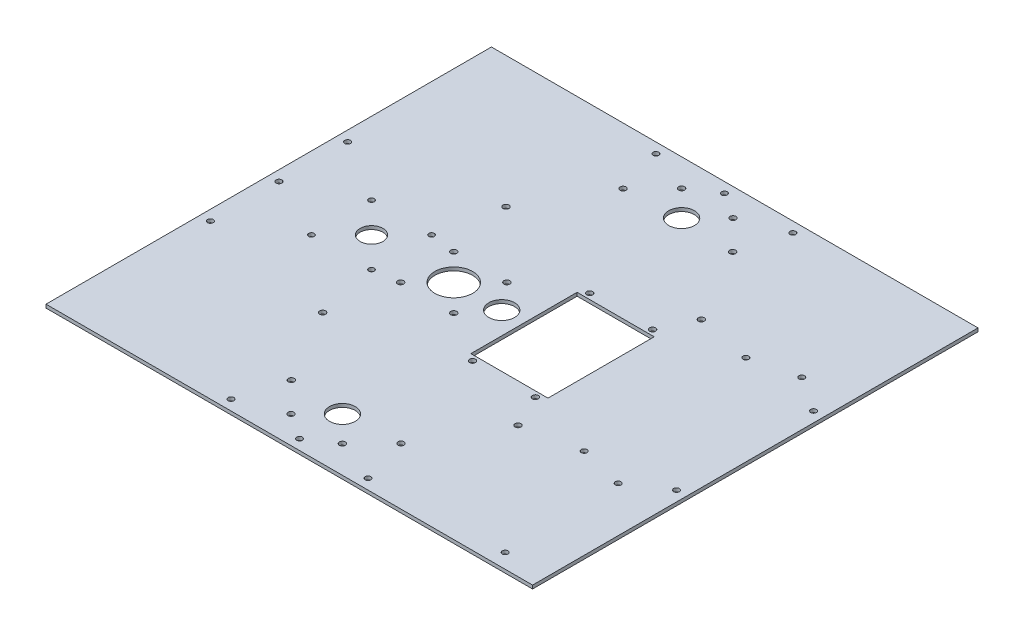
SolidWorks part; units mm, degrees
ref_plane "前视基准面" through (0, 0, 0) normal (0, 0, 1) x (1, 0, 0)
ref_plane "上视基准面" through (0, 0, 0) normal (0, 1, 0) x (1, 0, 0)
ref_plane "右视基准面" through (0, 0, 0) normal (1, 0, 0) x (0, 0, -1)
sketch "草图1" plane through (0, 0, 0) normal (0, 1, 0) x (1, 0, 0)
  line L0 (0, 130) -> (0, -35.361) construction
  line L1 (-142, -130) -> (142, -130)
  line L2 (-142, -130) -> (-142, 130)
  line L3 (-142, 130) -> (142, 130)
  line L5 (-142, 0) -> (204.6664, 0) construction
  line L10 (142, -130) -> (142, 130)
  dimension "D1" = 284
  dimension "D2" = 260
extrude "凸台-拉伸1" add sketch "草图1" along normal blind 2
sketch "草图2" plane through (0, 2, 0) normal (0, 1, 0) x (1, 0, 0)
  line L0 (-142, -130) -> (-142, 130) construction
  line L1 (-142, 0) -> (101.1534, 0) construction
  line L2 (-82, 0) -> (-86.8462, 4.8462) construction
  line L3 (142, 0) -> (52, 0) construction
  line L8 (50.3891, 31) -> (5.3891, -31) construction
  line L10 (-34, 21.5187) -> (-34, -23.7544) construction
  line L16 (52, -31) -> (7, -31)
  line L17 (52, -31) -> (52, 31)
  line L18 (52, 31) -> (7, 31)
  line L19 (-142, 130) -> (142, 130) construction
  line L20 (142, -130) -> (142, 130) construction
  line L21 (7, -31) -> (7, 31)
  line L24 (47.8891, 0) -> (29.5391, 0) construction
  line L25 (11.15, -34.2) -> (47.85, -34.2) construction
  line L26 (11.15, -34.2) -> (11.15, 34.2) construction
  circle A0 centre (-82, 0) radius 6.65
  circle A2 centre (-99.5362, 17.5362) radius 1.6
  circle A3 centre (-64.4638, 17.5362) radius 1.6
  circle A4 centre (-64.4638, -17.5362) radius 1.6
  circle A5 centre (-99.5362, -17.5362) radius 1.6
  circle A10 centre (-34, 0) radius 11.05
  circle A11 centre (-18.5, 15.5) radius 1.75
  circle A12 centre (-18.5, -15.5) radius 1.75
  circle A13 centre (-49.5, -15.5) radius 1.75
  circle A14 centre (-49.5, 15.5) radius 1.75
  circle A17 centre (-40, 124) radius 1.65
  circle A18 centre (0, 124) radius 1.65
  circle A19 centre (40, 124) radius 1.65
  circle A21 centre (117.5, -121.5) radius 1.65
  circle A22 centre (40, -124) radius 1.65
  circle A23 centre (0, -124) radius 1.65
  circle A24 centre (-40, -124) radius 1.65
  circle A25 centre (-136, 40) radius 1.65
  circle A26 centre (-136, -40) radius 1.65
  circle A27 centre (80, 124) radius 1.65 [skipped]
  circle A28 centre (-136, 0) radius 1.65
  circle A29 centre (136, 40) radius 1.65
  circle A30 centre (136, -40) radius 1.65
  circle A31 centre (115.5511, -53.6) radius 1.65
  circle A32 centre (89.3206, -47.2) radius 1.65
  circle A33 centre (115.5511, 53.6) radius 1.65
  circle A34 centre (89.3206, 47.2) radius 1.65
  circle A35 centre (11.15, -34.2) radius 1.75
  circle A36 centre (47.85, -34.2) radius 1.75
  circle A37 centre (47.85, 34.2) radius 1.75
  circle A38 centre (11.15, 34.2) radius 1.75
  point P20 (-82, 0)
  point P57 (47.8891, 0)
  dimension "D1" = 60
  dimension "D2" = 13.3
  dimension "D3" = 3.2
  dimension "D4" = 24.8
  dimension "D5" = 45
  dimension "D14" = 35.0725
  dimension "D15" = 35.0725
  dimension "D17" = 22.1
  dimension "D18" = 3.5
  dimension "D19" = 31
  dimension "D20" = 31
  dimension "D24" = 27
  dimension "D25" = 6.4
  dimension "D26" = 102
  dimension "D27" = 6
  dimension "D28" = 3.3
  dimension "D30" = 80
  dimension "D31" = 6
  dimension "D32" = 3.3
  dimension "D33" = 3.3
  dimension "D34" = 6
  dimension "D35" = 80
  dimension "D21" = 3.3
  dimension "D22" = 13.6
  dimension "D36" = 45
  dimension "D7" = 90
  dimension "D37" = 62
  dimension "D41" = 36.7
  dimension "D42" = 68.4
  dimension "D29" = 4
  dimension "D38" = 2
  dimension "D39" = 2
  dimension "D6" = 4
extrude "切除-拉伸1" cut sketch "草图2" against normal blind 10
sketch "草图3" plane through (0, 2, 0) normal (0, 1, 0) x (1, 0, 0)
  line L0 (0, -124) -> (0, -114) construction
  line L1 (0, -114) -> (15, -114) construction
  line L2 (0, 0) -> (38.3063, 0) construction
  circle A0 centre (15, -114) radius 1.75
  circle A1 centre (-15, -114) radius 1.75
  circle A2 centre (15, 114) radius 1.75
  circle A3 centre (-15, 114) radius 1.75
  dimension "D1" = 10
  dimension "D2" = 15
extrude "切除-拉伸2" cut sketch "草图3" against normal blind 10
sketch "草图4" plane through (0, 2, 0) normal (0, 1, 0) x (1, 0, 0)
  line L0 (0, 0) -> (-10, 0) construction
  line L1 (0, 124) -> (0, 99) construction
  circle A0 centre (-6, 0) radius 7.5
  circle A1 centre (0, 99) radius 7.5
  circle A2 centre (0, -99) radius 7.5
  dimension "D1" = 6
  dimension "D2" = 25
extrude "切除-拉伸3" cut sketch "草图4" against normal blind 10
sketch "草图5" plane through (0, 2, 0) normal (0, 1, 0) x (1, 0, 0)
  circle A1 centre (57.0027, 53.5) radius 1.75
  circle A2 centre (57.0027, 53.5) radius 1.75
  circle A3 centre (32.0027, 96.8013) radius 1.75
  circle A4 centre (32.0027, 96.8013) radius 1.75
  circle A5 centre (-32.0027, 96.8013) radius 1.75
  circle A6 centre (-32.0027, 96.8013) radius 1.75
  circle A7 centre (-57.0027, 53.5) radius 1.75
  circle A8 centre (-57.0027, 53.5) radius 1.75
  circle A9 centre (-57.0027, -53.5) radius 1.75
  circle A10 centre (-57.0027, -53.5) radius 1.75
  circle A11 centre (-32.0027, -96.8013) radius 1.75
  circle A12 centre (-32.0027, -96.8013) radius 1.75
  circle A13 centre (32.0027, -96.8013) radius 1.75
  circle A14 centre (32.0027, -96.8013) radius 1.75
  circle A15 centre (57.0027, -53.5) radius 1.75
  circle A16 centre (57.0027, -53.5) radius 1.75
  dimension "D1" = 0
  dimension "D2" = 0
  dimension "D3" = 0
  dimension "D4" = 0
  dimension "D5" = 0
  dimension "D6" = 0
  dimension "D7" = 0
  dimension "D8" = 0
extrude "切除-拉伸4" cut sketch "草图5" against normal blind 4.5
sketch "草图7" plane through (0, 0, 0) normal (0, -1, 0) x (-1, 0, 0)
  line L0 (82, 0) -> (34, 0) construction
